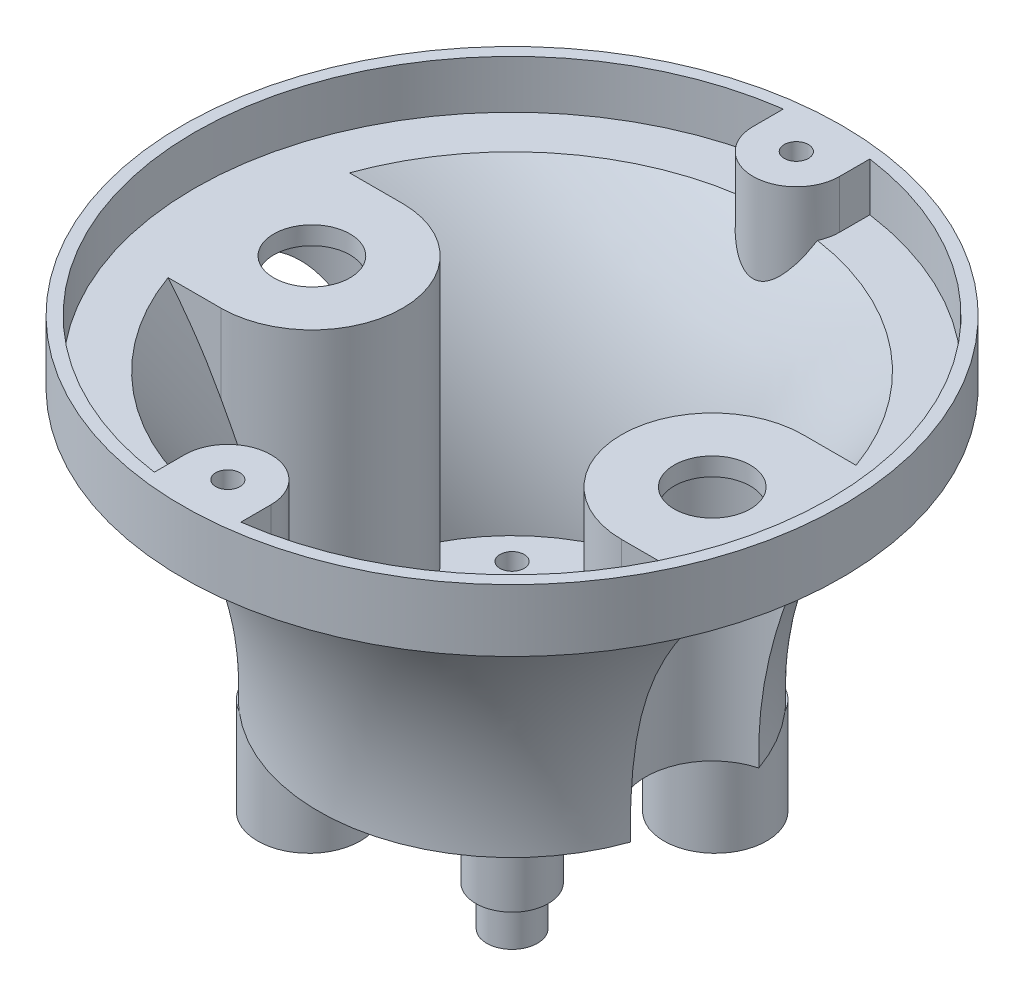
SolidWorks part; units mm, degrees
material "ABS"
ref_plane "Plan de face" through (0, 0, 0) normal (0, 0, 1) x (1, 0, 0)
ref_plane "Plan de dessus" through (0, 0, 0) normal (0, 1, 0) x (1, 0, 0)
ref_plane "Plan de droite" through (0, 0, 0) normal (1, 0, 0) x (0, 0, -1)
sketch "Esquisse1" plane through (0, 0, 0) normal (0, 0, 1) x (1, 0, 0)
  line L0 (0, 0) -> (0, 27.5) construction
  line L1 (0, 0) -> (16, 0)
  line L2 (27.25, 27.5) -> (26.25, 27.5)
  line L3 (27.25, 27.5) -> (27.25, 22.35)
  line L4 (27.25, 22.35) -> (23.25, 22.35)
  line L5 (26.25, 27.5) -> (26.25, 23.5)
  line L6 (26.25, 23.5) -> (22.2438, 23.5)
  line L7 (0, 0) -> (0, 23.5) construction
  line L8 (0, 1.5) -> (14.489, 1.5)
  line L9 (1.5, 1.5) -> (14.489, 1.5) construction
  line L10 (0, 0) -> (0, 1.5)
  line L13 (1.5, 1.5) -> (1.5, 22) construction
  line L15 (21.1304, 22) -> (1.5, 22) construction
  line L18 (26.25, 23.5) -> (0, 23.5) construction
  line L19 (21.1304, 22) -> (21.1304, 22) construction
  line L20 (21.1304, 22) -> (21.1304, 22) construction
  line L21 (21.1304, 22) -> (21.1304, 22) construction
  line L22 (21.1304, 22) -> (21.1304, 22) construction
  arc A0 (16, 0) -> (23.25, 22.35) centre (50.9857, 1.0021) cw
  arc A1 (14.489, 1.5) -> (22.2438, 23.5) centre (50.9857, 1.0021) cw
  arc A2 (14.489, 1.5) -> (21.1304, 22) centre (50.9857, 1.0021) cw construction
  dimension "D5" = 35
  dimension "D1" = 27.25
  dimension "D2" = 5.15
  dimension "D3" = 16
  dimension "D4" = 27.5
  dimension "D6" = 4
  dimension "D7" = 1
  dimension "D8" = 4
  dimension "D9" = 1.5
revolve "Révolution1" add sketch "Esquisse1" angle 360 about L0
sketch "Esquisse4" plane through (0, 27.5, 0) normal (0, 1, 0) x (1, 0, 0)
  line L0 (0, 0) -> (44.4289, 0) construction
  line L1 (-3.575, 23.5) -> (-3.575, 27.0145)
  line L2 (3.575, 23.5) -> (3.575, 27.0145)
  line L3 (3.575, -23.5) -> (3.575, -27.0145)
  line L4 (-3.575, -23.5) -> (-3.575, -27.0145)
  arc A0 (-3.575, 23.5) -> (3.575, 23.5) centre (0, 23.5) ccw
  circle A1 centre (0, 0) radius 27.25 construction
  circle A2 centre (0, 0) radius 27.25
  circle A3 centre (0, 23.5) radius 1
  circle A4 centre (0, -23.5) radius 1
  arc A5 (-3.575, -23.5) -> (3.575, -23.5) centre (0, -23.5) cw
  circle M1 centre (0, 0) radius 26.25
  circle M2 centre (0, 0) radius 27.25
  dimension "D1" = 23.5
  dimension "D3" = 2
  dimension "D2" = 7.15
extrude "Boss.-Extru.1" add sketch "Esquisse4" against normal up to next contours L1 A0 L2 A3 M1 | A5 L4 L3 A4 M1 | L4 L3 M1 M2
sketch "Esquisse5" plane through (0, 23.5, 0) normal (0, 1, 0) x (1, 0, 0)
  line L0 (-16.55, 7.5) -> (-20.9413, 7.5)
  line L1 (-16.55, -7.5) -> (-20.9413, -7.5)
  line L2 (0, 0) -> (0, 39.6072) construction
  line L3 (16.55, -7.5) -> (20.9413, -7.5)
  line L4 (16.55, 7.5) -> (20.9413, 7.5)
  arc A0 (-16.55, -7.5) -> (-16.55, 7.5) centre (-16.55, 0) ccw
  circle A1 centre (-16.55, 0) radius 3.15
  arc A2 (-3.2476, 22.0055) -> (-3.2476, -22.0055) centre (0, 0) ccw construction
  arc A3 (-20.9413, 7.5) -> (-20.9413, -7.5) centre (0, 0) ccw
  arc A4 (20.9413, 7.5) -> (20.9413, -7.5) centre (0, 0) cw
  circle A5 centre (16.55, 0) radius 3.15
  arc A6 (16.55, -7.5) -> (16.55, 7.5) centre (16.55, 0) cw
  dimension "D1" = 15
  dimension "D3" = 6.3
  dimension "D2" = 16.55
extrude "Boss.-Extru.2" add sketch "Esquisse5" against normal up to next
sketch "Esquisse6" plane through (0, 0, 0) normal (0, -1, 0) x (1, 0, 0)
  circle A0 centre (0, 0) radius 5.15
  dimension "D1" = 10.3
extrude "Enlèv. mat.-Extru.2" cut sketch "Esquisse6" against normal blind 22
sketch "Esquisse8" plane through (0, 23.5, 0) normal (0, 1, 0) x (1, 0, 0)
  line L0 (0, 0) -> (-23.7608, 0) construction
  circle A2 centre (-16.55, 0) radius 3.15
  circle A3 centre (16.55, 0) radius 3.15
  dimension "D3" = 6.3
  dimension "D1" = 33.1
  dimension "D2" = 16.55
extrude "Enlèv. mat.-Extru.3" cut sketch "Esquisse8" against normal through all
sketch "Esquisse9" plane through (0, 0, 0) normal (0, -1, 0) x (-1, 0, 0)
  line L0 (0, 0) -> (0, -29.2077) construction
  line L1 (0, 0) -> (40.9509, 0) construction
  circle A0 centre (16.55, 0) radius 5.5
  circle A1 centre (-16.55, 0) radius 5.5
  dimension "D1" = 11
  dimension "D3" = 16.55
extrude "Enlèv. mat.-Extru.5" cut sketch "Esquisse9" against normal blind 22
sketch "Esquisse10" plane through (0, 0, 0) normal (0, -1, 0) x (1, 0, 0)
  line L0 (-11.3137, 11.3137) -> (11.3137, -11.3137) construction
  line L1 (0, 0) -> (0, 44.1463) construction
  line L2 (8.4004, 8.4004) -> (-35.7735, -35.7735) construction
  line L3 (0, 0) -> (-56.2503, 0) construction
  circle A0 centre (-8.3969, 8.3969) radius 4.25
  arc A1 (15.0952, 5.3041) -> (-15.0952, 5.3041) centre (0, 0) ccw construction
  circle A2 centre (8.4004, 8.4004) radius 3
  arc A3 (-15.0952, -5.3041) -> (15.0952, -5.3041) centre (0, 0) ccw construction
  circle A4 centre (8.4004, -8.4004) radius 4.25
  circle A5 centre (-8.3969, -8.3969) radius 3
  dimension "D1" = 8.5
  dimension "D2" = 6
  dimension "D5" = 11.88
  dimension "D3" = 45
  dimension "D4" = 45
  dimension "D6" = 11.875
  dimension "D7" = 11.875
extrude "Boss.-Extru.3" add sketch "Esquisse10" along normal blind 8
sketch "Esquisse11" plane through (0, -8, 0) normal (0, -1, 0) x (1, 0, 0)
  circle A0 centre (-8.3969, 8.3969) radius 1.5
  circle A1 centre (8.4004, -8.4004) radius 1.5
  dimension "D1" = 3
extrude "Enlèv. mat.-Extru.6" cut sketch "Esquisse11" against normal through all
sketch "Esquisse12" plane through (0, -8, 0) normal (0, -1, 0) x (1, 0, 0)
  circle A0 centre (-8.3969, -8.3969) radius 1
  circle A1 centre (8.4004, 8.4004) radius 1
  dimension "D1" = 2
extrude "Enlèv. mat.-Extru.7" cut sketch "Esquisse12" against normal through all
sketch "Esquisse13" plane through (0, -8, 0) normal (0, -1, 0) x (1, 0, 0)
  circle A0 centre (8.4004, 8.4004) radius 2.1
  circle A1 centre (-8.3969, -8.3969) radius 2.1
  circle A2 centre (-8.3969, -8.3969) radius 3 construction
  circle A3 centre (8.4004, 8.4004) radius 3 construction
  circle A4 centre (-8.3969, -8.3969) radius 3
  circle A5 centre (8.4004, 8.4004) radius 3
  dimension "D1" = 4.2
extrude "Enlèv. mat.-Extru.8" cut sketch "Esquisse13" against normal blind 3.3
